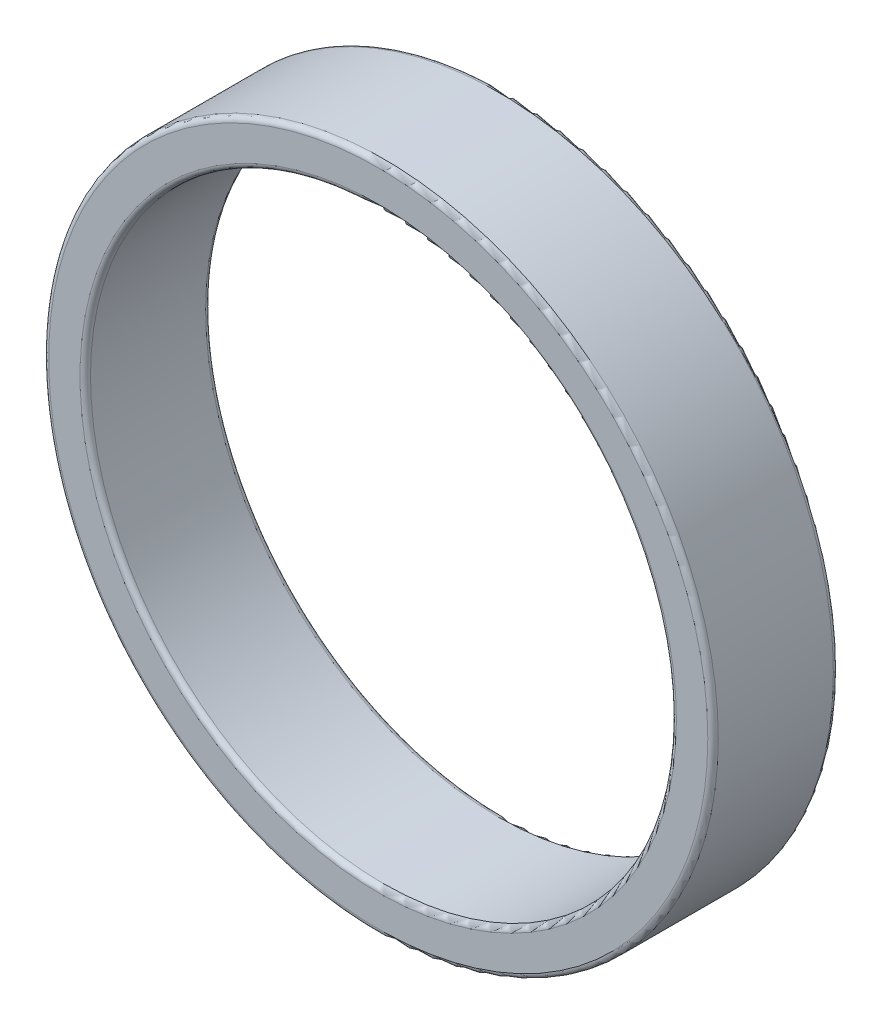
SolidWorks part; units mm, degrees
ref_plane "Front Plane" through (0, 0, 0) normal (0, 0, 1) x (1, 0, 0)
ref_plane "Top Plane" through (0, 0, 0) normal (0, 1, 0) x (1, 0, 0)
ref_plane "Right Plane" through (0, 0, 0) normal (1, 0, 0) x (0, 0, -1)
sketch "Sketch1" plane through (0, 0, 0) normal (0, 0, 1) x (1, 0, 0)
  circle A0 centre (0, 0) radius 14
  dimension "D1" = 28
extrude "Extrude-Thin1" add sketch "Sketch1" along normal blind 6 thin
fillet "Fillet1" radius 0.25 4 edges at (14, 0, 0) (16, 0, 0) (14, 0, 6) (16, 0, 6)
